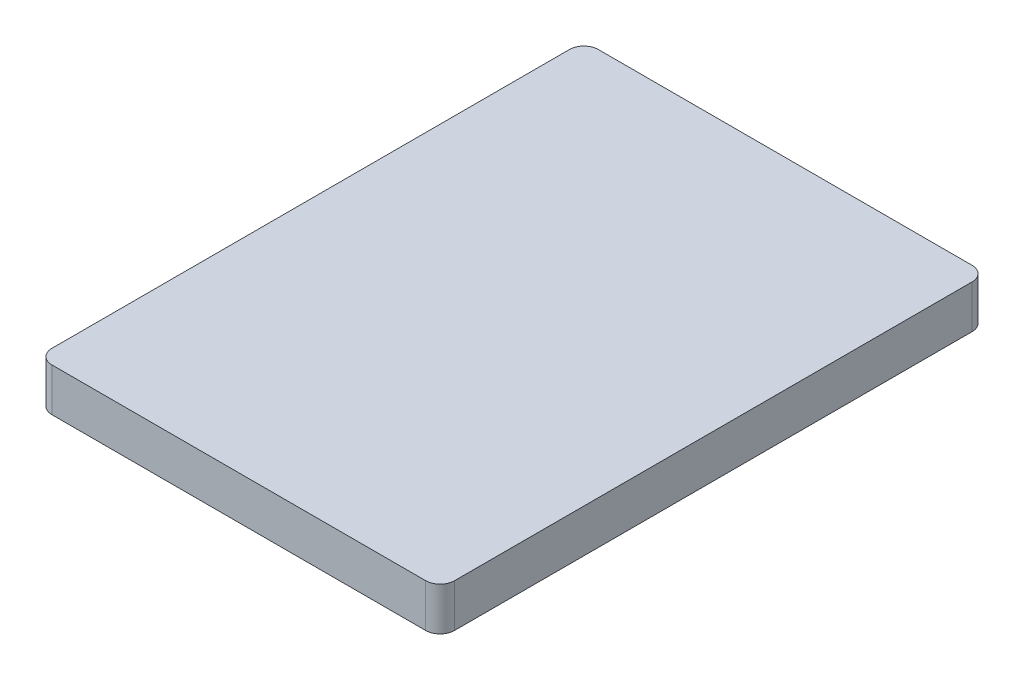
SolidWorks part; units mm, degrees
ref_plane "前视基准面" through (0, 0, 0) normal (0, 0, 1) x (1, 0, 0)
ref_plane "上视基准面" through (0, 0, 0) normal (0, 1, 0) x (1, 0, 0)
ref_plane "右视基准面" through (0, 0, 0) normal (1, 0, 0) x (0, 0, -1)
other "Configuration Table"
sketch "草图1" plane through (0, 0, 0) normal (0, 0, 1) x (1, 0, 0)
  line L0 (0, 0) -> (56, 0)
  line L1 (56, 0) -> (56, 6)
  line L2 (56, 6) -> (0, 6)
  line L3 (0, 6) -> (0, 0)
  dimension "width" = 56
  dimension "height" = 6
extrude "Support_plate" add sketch "草图1" along normal blind 76
fillet "Fillet" radius 2 4 edges at (0, 3, 0) (56, 3, 0) (0, 3, 76) (56, 3, 76)
